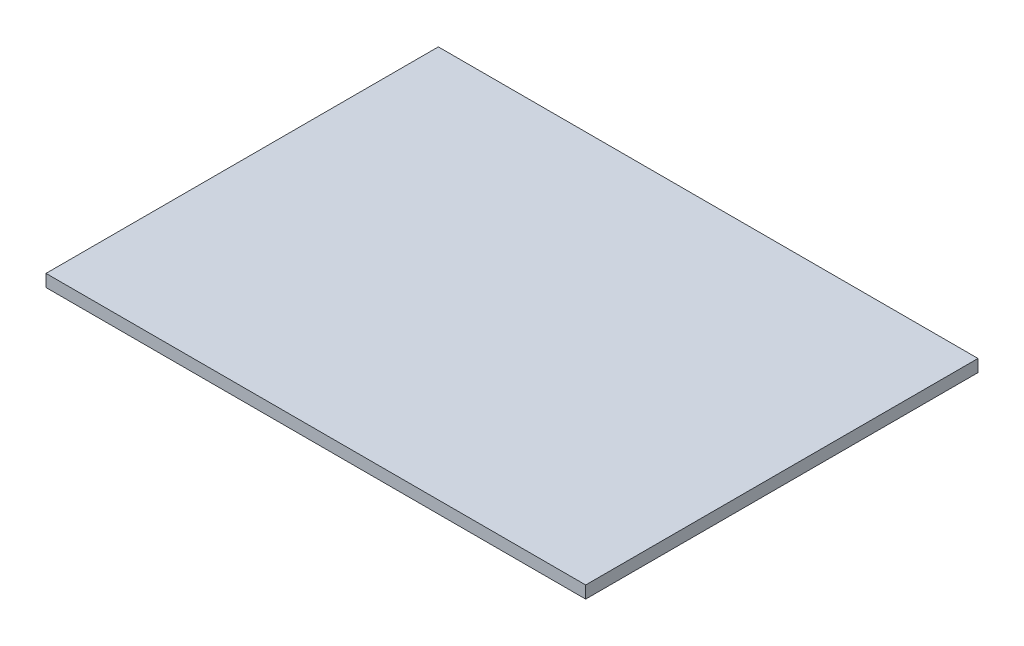
SolidWorks part; units mm, degrees
material "Pine"
ref_plane "Front Plane" through (0, 0, 0) normal (0, 0, 1) x (1, 0, 0)
ref_plane "Top Plane" through (0, 0, 0) normal (0, 1, 0) x (1, 0, 0)
ref_plane "Right Plane" through (0, 0, 0) normal (1, 0, 0) x (0, 0, -1)
sketch "Sketch1" plane through (0, 0, 0) normal (1, 0, 0) x (0, 0, -1)
  line L5 (0, 0) -> (203.1136, 0)
  line L6 (0, 0) -> (0, -6.36)
  line L7 (0, -6.36) -> (203.1136, -6.36)
  line L8 (203.1136, 0) -> (203.1136, -6.36)
extrude "Boss-Extrude1" add sketch "Sketch1" along normal blind 279.4
sketch "Sketch2" plane through (0, 0, 0) normal (0, 1, 0) x (1, 0, 0)
  point P0 (10.1037, 192.2554)
  point P1 (32.0246, 192.2554)
  point P2 (226.0749, 192.2554)
  point P3 (260.8107, 192.2554)
